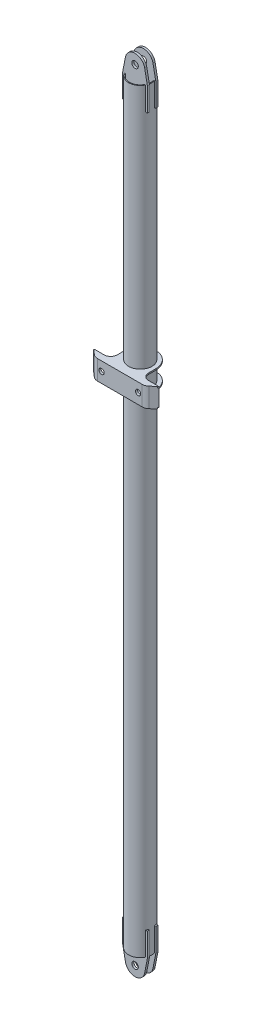
SolidWorks part; units mm, degrees
ref_plane "前视基准面" through (0, 0, 0) normal (0, 0, 1) x (1, 0, 0)
ref_plane "上视基准面" through (0, 0, 0) normal (0, 1, 0) x (1, 0, 0)
ref_plane "右视基准面" through (0, 0, 0) normal (1, 0, 0) x (0, 0, -1)
sketch "草图1" plane through (0, 0, 0) normal (0, 1, 0) x (1, 0, 0)
  circle A0 centre (0, 0) radius 84
  circle A1 centre (0, 0) radius 90
  dimension "D1" = 180
  dimension "D2" = 168
extrude "凸台-拉伸1" add sketch "草图1" along normal blind 5795
sketch "草图2" plane through (0, 5795, 0) normal (0, 1, 0) x (1, 0, 0)
  line L0 (-1000, 0) -> (49000, 0) construction
  line L1 (0, -1000) -> (0, 49000) construction
  line L2 (-90, 40) -> (90, 40)
  line L3 (-90, 40) -> (-90, 24)
  line L4 (-90, 24) -> (90, 24)
  line L5 (90, 40) -> (90, 24)
  line L6 (-90, -24) -> (90, -24)
  line L7 (-90, -24) -> (-90, -40)
  line L8 (-90, -40) -> (90, -40)
  line L9 (90, -24) -> (90, -40)
  dimension "D1" = 80
  dimension "D2" = 48
  dimension "D3" = 40
  dimension "D4" = 24
  dimension "D5" = 90
  dimension "D6" = 90
extrude "切除-拉伸1" cut sketch "草图2" against normal blind 180
sketch "草图3" plane through (0, 5615, 0) normal (0, 1, 0) x (1, 0, 0)
  line L0 (-86.741, 24) -> (-80.4984, 24) construction
  line L1 (-95, 40) -> (95, 40)
  line L2 (-95, 40) -> (-95, 24)
  line L3 (-95, 24) -> (95, 24)
  line L4 (95, 40) -> (95, 24)
  line L5 (-95, -24) -> (95, -24)
  line L6 (-95, -24) -> (-95, -40)
  line L7 (-95, -40) -> (95, -40)
  line L8 (95, -24) -> (95, -40)
  line L9 (-73.8647, 40) -> (-80.6226, 40) construction
  line L10 (-80.4984, -24) -> (-86.741, -24) construction
  line L11 (-80.6226, -40) -> (-73.8647, -40) construction
  dimension "D1" = 95
  dimension "D2" = 190
extrude "凸台-拉伸2" add sketch "草图3" along normal blind 400
sketch "草图4" plane through (0, 0, -40) normal (0, 0, -1) x (-1, 0, 0)
  line L0 (95, 5795) -> (95, 6015)
  line L1 (95, 6015) -> (95, 5615) construction
  line L2 (95, 6015) -> (-95, 6015)
  line L3 (-95, 6015) -> (-95, 5795)
  line L4 (-95, 6015) -> (-95, 5615) construction
  line L5 (-95, 5795) -> (-73.6056, 5904.3951)
  line L6 (95, 5795) -> (73.6056, 5904.3951)
  line L7 (80.6226, 5615) -> (95, 5615) construction
  line L8 (0, 5015) -> (0, 55015) construction
  arc A0 (-73.6056, 5904.3951) -> (73.6056, 5904.3951) centre (0, 5890) cw
  circle A1 centre (0, 5890) radius 25
  point P18 (0, 6015)
  dimension "D3" = 75
  dimension "D4" = 50
  dimension "D1" = 180
  dimension "D2" = 275
extrude "切除-拉伸2" cut sketch "草图4" against normal through all
ref_plane "基准面1" through (0, 2897.5, 0) normal (0, 1, 0) x (1, 0, 0)
mirror "镜向1" about plane through (0, 2897.5, 0) normal (0, 1, 0) of "切除-拉伸2", "凸台-拉伸2", "切除-拉伸1"
ref_plane "基准面2" through (0, 3760, 0) normal (0, 1, 0) x (1, 0, 0)
sketch "草图5" plane through (0, 3760, 0) normal (0, 1, 0) x (1, 0, 0)
  line L0 (170, -107) -> (240, -107)
  line L1 (-170, -107) -> (-240, -107)
  line L2 (-120, 0) -> (-120, -57)
  line L3 (120, 0) -> (120, -57)
  line L4 (-171.0156, -157) -> (171.0156, -157)
  line L5 (-240, -107) -> (-245, -112)
  line L6 (-245, -112) -> (-209.6239, -142.614)
  line L7 (240, -107) -> (245, -112)
  line L8 (245, -112) -> (209.6239, -142.614)
  line L9 (0, -1000) -> (0, 49000) construction
  circle A0 centre (0, 0) radius 90
  arc A1 (80.6226, 40) -> (-80.6226, 40) centre (0, 0) ccw construction
  arc A2 (-120, 0) -> (120, 0) centre (0, 0) cw
  arc A3 (120, -57) -> (170, -107) centre (170, -57) ccw
  arc A4 (-120, -57) -> (-170, -107) centre (-170, -57) cw
  arc A5 (-171.0156, -157) -> (-209.6239, -142.614) centre (-171.0156, -98) cw
  arc A6 (209.6239, -142.614) -> (171.0156, -157) centre (171.0156, -98) cw
  point P24 (-193, -157)
  point P27 (193, -157)
  dimension "D1" = 120
  dimension "D2" = 50
  dimension "D3" = 50
  dimension "D12" = 59
  dimension "D15" = 59
  dimension "D4" = 107
  dimension "D5" = 193
  dimension "D6" = 193
  dimension "D7" = 50
  dimension "D8" = 245
  dimension "D9" = 245
  dimension "D10" = 5
  dimension "D11" = 5
  dimension "D13" = 5
  dimension "D14" = 5
extrude "凸台-拉伸3" add sketch "草图5" along normal blind 10
pattern_linear "阵列(线性)1" count 2 spacing 140 along (0, 1, 0) of "凸台-拉伸3"
sketch "草图6" plane through (0, 3900, 0) normal (0, -1, 0) x (1, 0, 0)
  line L0 (-250, 107.6731) -> (-239.53, 95.5744)
  line L1 (-171.0156, 157) -> (171.0156, 157)
  line L2 (-171.0156, 157) -> (171.0156, 157) construction
  line L3 (0, -1000) -> (0, 49000) construction
  line L4 (-250, 107.6731) -> (-209.6239, 142.614)
  line L5 (250, 107.6731) -> (209.6239, 142.614)
  line L6 (209.6239, 142.614) -> (245, 112) construction
  line L7 (-245, 112) -> (-209.6239, 142.614) construction
  line L8 (-239.53, 95.5744) -> (-203.662, 126.614)
  line L9 (-165.0538, 141) -> (165.0538, 141)
  line L10 (203.662, 126.614) -> (239.53, 95.5744)
  line L11 (239.53, 95.5744) -> (250, 107.6731)
  arc A0 (-171.0156, 157) -> (-209.6239, 142.614) centre (-171.0156, 98) ccw
  arc A1 (203.662, 126.614) -> (165.0538, 141) centre (165.0538, 82) ccw
  arc A2 (209.6239, 142.614) -> (171.0156, 157) centre (171.0156, 98) ccw
  arc A3 (-165.0538, 141) -> (-203.662, 126.614) centre (-165.0538, 82) ccw
  dimension "D6" = 59
  dimension "D7" = 16
  dimension "D8" = 59
  dimension "D9" = 59
  dimension "D5" = 59
  dimension "D1" = 250
  dimension "D2" = 250
  dimension "D3" = 16
  dimension "D4" = 16
extrude "凸台-拉伸4" add sketch "草图6" along normal blind 130
sketch "草图7" plane through (0, 0, 157) normal (0, 0, 1) x (1, 0, 0)
  line L0 (0, 4890) -> (0, 54890) construction
  line L1 (-171.0156, 3760) -> (171.0156, 3760) construction
  circle A0 centre (-140, 3840) radius 20
  circle A1 centre (140, 3840) radius 20
  dimension "D1" = 40
  dimension "D2" = 40
  dimension "D3" = 140
  dimension "D4" = 140
  dimension "D5" = 80
extrude "切除-拉伸3" cut sketch "草图7" against normal blind 16
